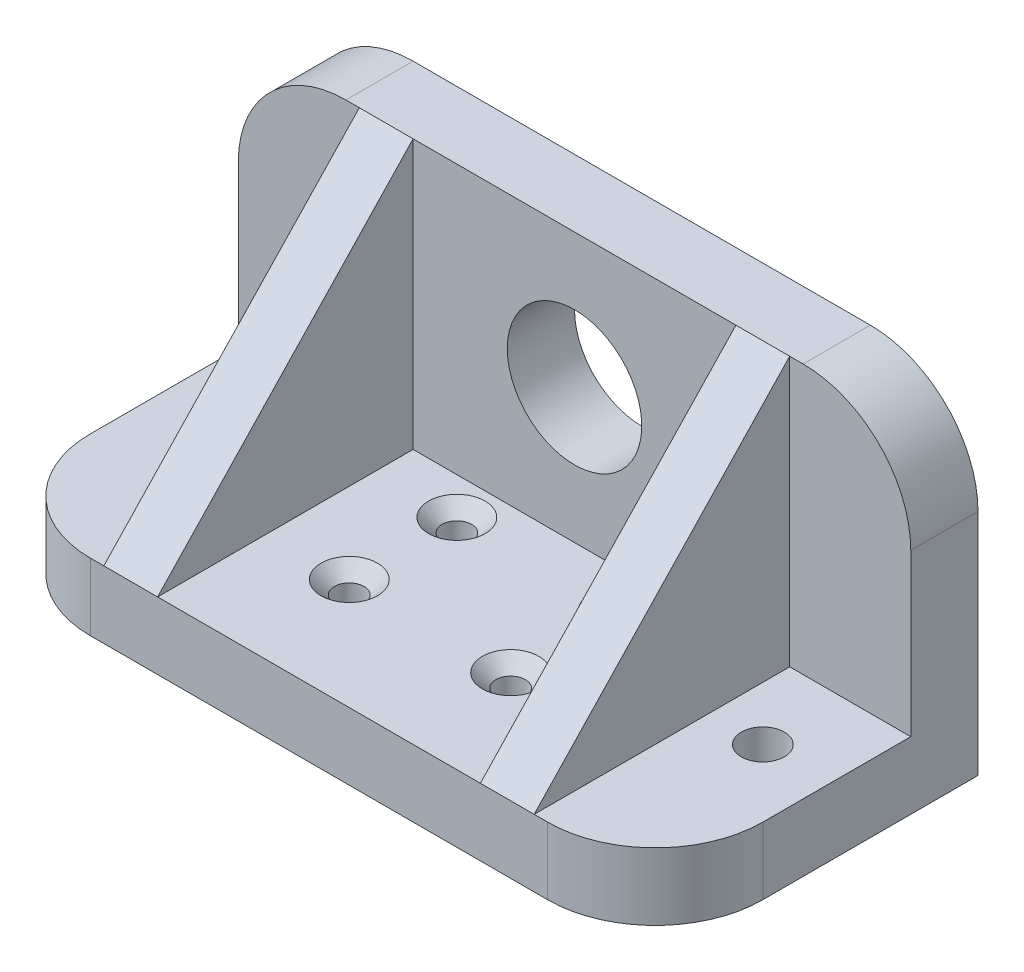
SolidWorks part; units mm, degrees
material "ABS"
ref_plane "前视基准面" through (0, 0, 0) normal (0, 0, 1) x (1, 0, 0)
ref_plane "上视基准面" through (0, 0, 0) normal (0, 1, 0) x (1, 0, 0)
ref_plane "右视基准面" through (0, 0, 0) normal (1, 0, 0) x (0, 0, -1)
sketch "草图1" plane through (0, 0, 0) normal (0, 1, 0) x (1, 0, 0)
  line L1 (-25, -12) -> (25, -12)
  line L2 (-25, -12) -> (-25, 12)
  line L3 (-25, 12) -> (25, 12)
  line L4 (25, -12) -> (25, 12)
  line L5 (-25, -12) -> (25, 12) construction
  line L6 (-25, 12) -> (25, -12) construction
  point P0 (0, 0)
  dimension "D1" = 50
  dimension "D2" = 24
extrude "凸台-拉伸1" add sketch "草图1" along normal blind 5
sketch "草图2" plane through (0, 5, 0) normal (0, 1, 0) x (1, 0, 0)
  line L0 (25, -12) -> (25, 12) construction
  line L1 (-25, 12) -> (25, 12)
  line L2 (-25, 12) -> (-25, 7)
  line L3 (-25, 7) -> (25, 7)
  line L4 (25, 12) -> (25, 7)
  dimension "D1" = 5
extrude "凸台-拉伸2" add sketch "草图2" along normal blind 20
sketch "草图3" plane through (0, 5, 0) normal (0, 1, 0) x (1, 0, 0)
  line L0 (0, 7) -> (0, -12) construction
  line L1 (-25, 7) -> (25, 7) construction
  line L2 (-25, -12) -> (25, -12) construction
  line L3 (16, -12) -> (12, -12)
  line L4 (-16, 7) -> (-12, 7)
  line L5 (-16, 7) -> (-16, -12)
  line L6 (-16, -12) -> (-12, -12)
  line L7 (-12, 7) -> (-12, -12)
  line L8 (12, 7) -> (12, -12)
  line L9 (16, 7) -> (12, 7)
  line L10 (16, 7) -> (16, -12)
  dimension "D1" = 4
  dimension "D2" = 12
extrude "凸台-拉伸3" add sketch "草图3" along normal blind 20
sketch "草图4" plane through (-16, 0, 0) normal (-1, 0, 0) x (0, 0, 1)
  line L0 (-7, 25) -> (12, 5)
  line L1 (12, 5) -> (12, 25)
  line L2 (12, 25) -> (-7, 25)
extrude "切除-拉伸1" cut sketch "草图4" against normal through all
sketch "草图6" plane through (0, 5, 0) normal (0, 1, 0) x (1, 0, 0)
  line L0 (0, 7) -> (0, -12) construction
  line L1 (-12, 7) -> (12, 7) construction
  line L2 (-12, -12) -> (12, -12) construction
  line L4 (-12, 7) -> (12, 7) construction
  line L5 (-6, -3.75) -> (6, -3.75) construction
  line L6 (-6, -3.75) -> (-6, 4.25) construction
  line L7 (-6, 4.25) -> (6, 4.25) construction
  line L8 (6, -3.75) -> (6, 4.25) construction
  line L9 (-6, -3.75) -> (6, 4.25) construction
  line L10 (-6, 4.25) -> (6, -3.75) construction
  circle A0 centre (6, 4.25) radius 1.1
  circle A1 centre (6, -3.75) radius 1.1
  circle A2 centre (-6, 4.25) radius 1.1
  circle A3 centre (-6, -3.75) radius 1.1
  point P8 (0, 0.25)
  dimension "D2" = 2.2
  dimension "D5" = 2.2
  dimension "D1" = 2.75
  dimension "D3" = 12
  dimension "D4" = 8
extrude "切除-拉伸2" cut sketch "草图6" against normal through all
sketch "草图7" plane through (0, 0, -12) normal (0, 0, -1) x (-1, 0, 0)
  line L0 (0, 25) -> (0, 0) construction
  line L1 (-25, 25) -> (25, 25) construction
  line L2 (-25, 0) -> (25, 0) construction
  circle A0 centre (0, 15) radius 5
  dimension "D1" = 10
  dimension "D2" = 15
extrude "切除-拉伸3" cut sketch "草图7" against normal through all
sketch "草图8" plane through (0, 5, 0) normal (0, 1, 0) x (1, 0, 0)
  line L0 (0, 12) -> (0, -12) construction
  line L1 (25, 12) -> (-25, 12) construction
  line L2 (-12, -12) -> (12, -12) construction
  line L3 (16, 7) -> (25, 7) construction
  circle A0 centre (20, 1) radius 1.6
  circle A1 centre (-20, 1) radius 1.6
  dimension "D1" = 3.2
  dimension "D2" = 20
  dimension "D3" = 6
extrude "切除-拉伸4" cut sketch "草图8" against normal through all
fillet "圆角1" radius 8 4 edges at (25, 25, -9.5) (25, 2.5, 12) (-25, 2.5, 12) (-25, 25, -9.5)
chamfer "倒角1" distance 1 angle 45 4 edges at (6, 5, 4.85) (-6, 5, 2.65) (6, 5, -3.15) (-6, 5, -5.35)
